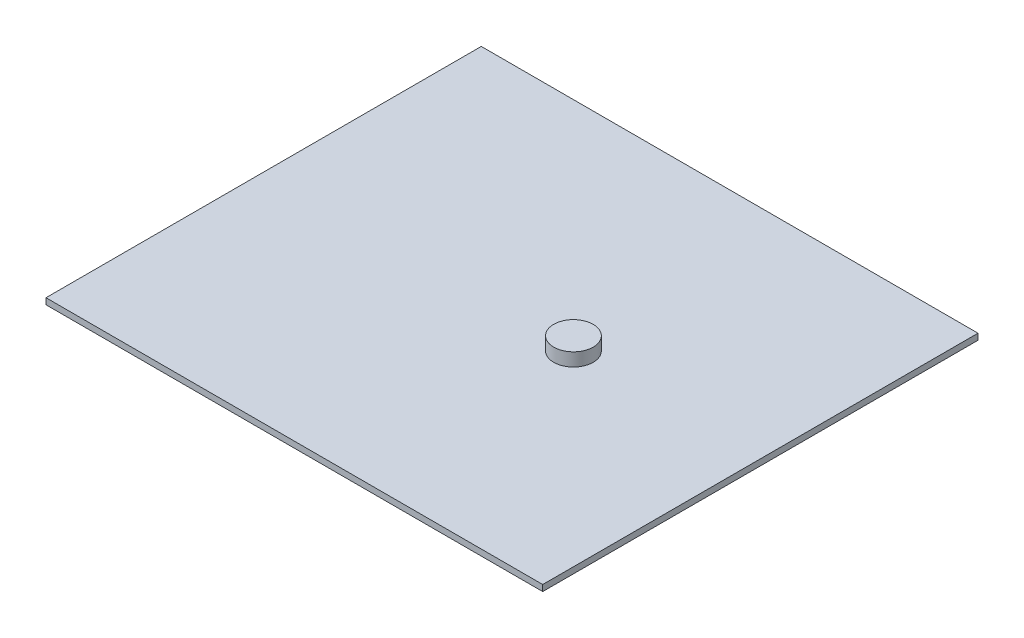
SolidWorks part; units mm, degrees
ref_plane "Front Plane" through (0, 0, 0) normal (0, 0, 1) x (1, 0, 0)
ref_plane "Top Plane" through (0, 0, 0) normal (0, 1, 0) x (1, 0, 0)
ref_plane "Right Plane" through (0, 0, 0) normal (1, 0, 0) x (0, 0, -1)
sketch "Sketch1" plane through (0, 0, 0) normal (0, 1, 0) x (1, 0, 0)
  line L0 (-282.94, -247.94) -> (-282.94, 247.94)
  line L1 (-282.94, -247.94) -> (282.94, -247.94)
  line L2 (-282.94, 247.94) -> (282.94, 247.94)
  line L3 (282.94, -247.94) -> (282.94, 247.94)
  line L4 (-282.94, -247.94) -> (282.94, 247.94) construction
  line L5 (-282.94, 247.94) -> (282.94, -247.94) construction
  point P1 (0, 0)
  dimension "D1" = 565.88
  dimension "D2" = 495.88
extrude "Boss-Extrude1" add sketch "Sketch1" along normal mid plane 7
sketch "Sketch2" plane through (0, 3.5, 0) normal (0, 1, 0) x (1, 0, 0)
  line L0 (70, -247.94) -> (70, 247.94) construction
  line L1 (282.94, 247.94) -> (-282.94, 247.94) construction
  circle A0 centre (70, 0) radius 22.5
  point P5 (70, 0)
  dimension "D2" = 45
  dimension "D1" = 70
extrude "Boss-Extrude2" add sketch "Sketch2" along normal blind 15
